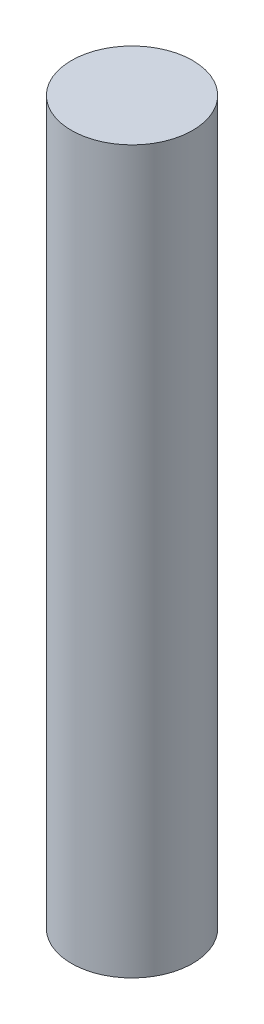
SolidWorks part; units mm, degrees
material "Plain Carbon Steel"
ref_plane "Front Plane" through (0, 0, 0) normal (0, 0, 1) x (1, 0, 0)
ref_plane "Top Plane" through (0, 0, 0) normal (0, 1, 0) x (1, 0, 0)
ref_plane "Right Plane" through (0, 0, 0) normal (1, 0, 0) x (0, 0, -1)
sketch "Sketch1" plane through (0, 0, 0) normal (0, 1, 0) x (1, 0, 0)
  circle A0 centre (0, 0) radius 1.6002
  dimension "D1" = 3.2004
extrude "Boss-Extrude1" add sketch "Sketch1" along normal blind 19.05
